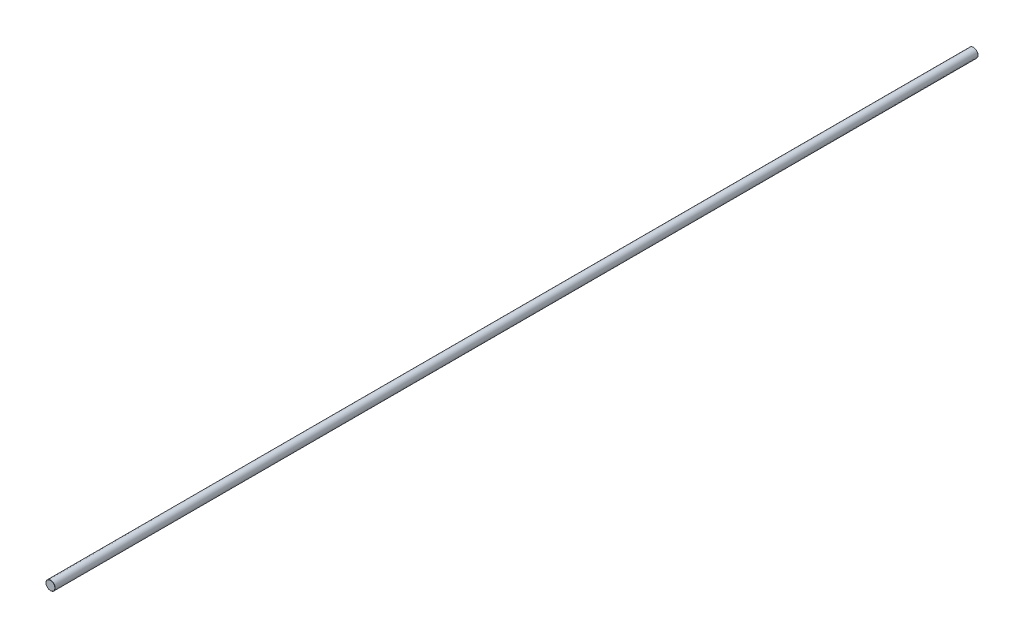
SolidWorks part; units mm, degrees
ref_plane "Front Plane" through (0, 0, 0) normal (0, 0, 1) x (1, 0, 0)
ref_plane "Top Plane" through (0, 0, 0) normal (0, 1, 0) x (1, 0, 0)
ref_plane "Right Plane" through (0, 0, 0) normal (1, 0, 0) x (0, 0, -1)
sketch "Sketch1" plane through (0, 0, 0) normal (0, 0, 1) x (1, 0, 0)
  circle A0 centre (0, 0) radius 5 construction
  dimension "Diameter" = 10
sketch "Sketch2" plane through (0, 0, 0) normal (1, 0, 0) x (0, 0, -1)
  line L0 (500, 0) -> (-500, 0) construction
  point P0 (-400, 0)
  point P3 (0, 0)
  point P4 (400, 0)
  point P6 (-350, 0)
  point P7 (350, 0)
  dimension "Length" = 1000
  dimension "D1" = 100
  dimension "D2" = 100
  dimension "D3" = 150
  dimension "D4" = 150
sketch "Sketch3" plane through (0, 0, 0) normal (0, 0, 1) x (1, 0, 0)
  circle A0 centre (0, 0) radius 5 construction
  circle A1 centre (0, 0) radius 5
extrude "Boss-Extrude1" add sketch "Sketch3" along normal up to vertex (500 mm away) and the other way up to vertex (500 mm away) up to point (0, 0, 500) other way up to point (0, 0, -500)
chamfer "Chamfer1" distance 0.2 angle 45 2 edges at (5, 0, 500) (5, 0, -500)
equation "\"D1@Chamfer1\"=\"Diameter@Sketch1\"*.02"
equation "\"D1@Sketch2\"=\"D2@Sketch2\""
equation "\"D2@Sketch2\"=\"Length@Sketch2\"*.1"
equation "\"D3@Sketch2\"=\"Length@Sketch2\"*.15"
equation "\"D4@Sketch2\"=\"D3@Sketch2\""
